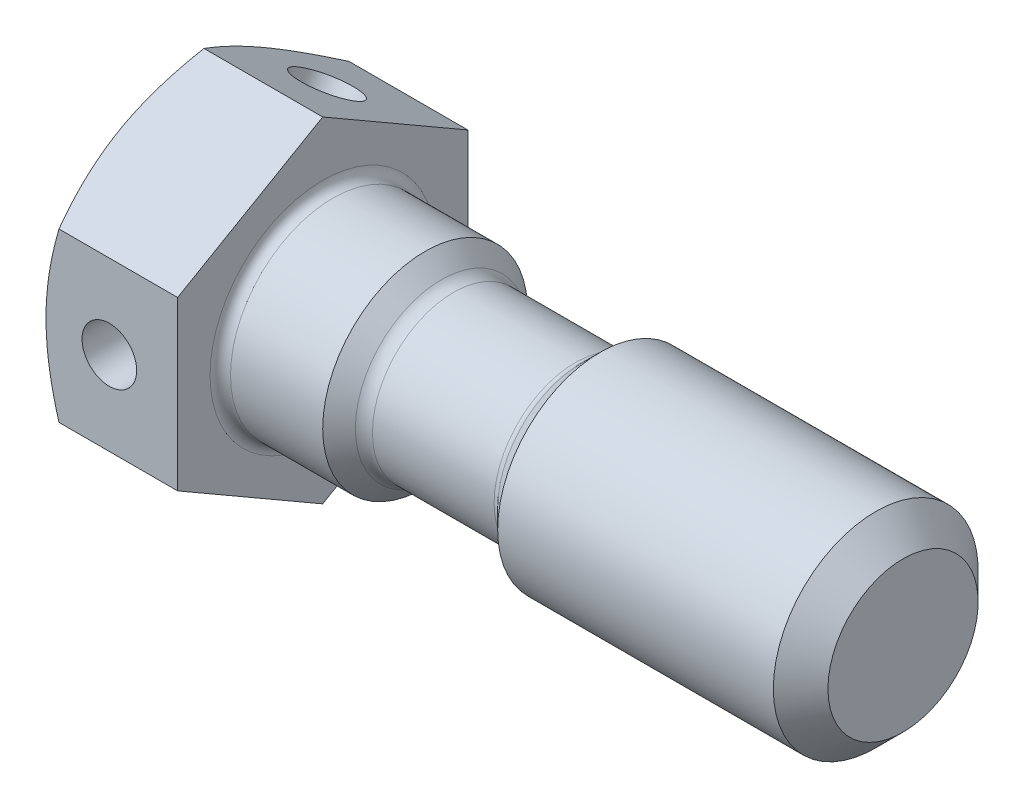
SolidWorks part; units mm, degrees
material "Простая углеродистая сталь"
ref_plane "Спереди" through (0, 0, 0) normal (0, 0, 1) x (1, 0, 0)
ref_plane "Сверху" through (0, 0, 0) normal (0, 1, 0) x (1, 0, 0)
ref_plane "Справа" through (0, 0, 0) normal (1, 0, 0) x (0, 0, -1)
sketch "Эскиз1" plane through (0, 0, 0) normal (0, 0, 1) x (1, 0, 0)
  line L0 (0, 0) -> (41.4975, 0) construction
  line L1 (0, 0) -> (0, 6)
  line L2 (0, 6) -> (6, 6)
  line L3 (6, 6) -> (6.9571, 5.0429)
  line L4 (7.6642, 4.75) -> (14.7929, 4.75)
  line L5 (15.1464, 4.8964) -> (16.25, 6)
  line L6 (16.25, 6) -> (32.4, 6)
  line L7 (34, 4.4) -> (34, 0)
  line L8 (34, 0) -> (0, 0)
  line L9 (32.4, 6) -> (34, 4.4)
  arc A0 (7.6642, 4.75) -> (6.9571, 5.0429) centre (7.6642, 5.75) cw
  arc A1 (15.1464, 4.8964) -> (14.7929, 4.75) centre (14.7929, 5.25) cw
  point P3 (34, 6)
  point P16 (15, 4.75)
  dimension "D10" = 1
  dimension "D11" = 0.5
  dimension "D1" = 12
  dimension "D2" = 9.5
  dimension "D3" = 12
  dimension "D4" = 45
  dimension "D5" = 6
  dimension "D6" = 19
  dimension "D7" = 34
  dimension "D8" = 1.6
  dimension "D9" = 45
revolve "Повернуть1" add sketch "Эскиз1" angle 360 about L0
cosmetic thread "Условное изображение резьбы1" parameters "D2"=10.072
sketch "Эскиз2" plane through (0, 0, 0) normal (-1, 0, 0) x (0, 0, 1)
  line L0 (-8.5, 0) -> (8.5, 0) construction
  line L1 (0, -9.815) -> (0, 9.815) construction
  line L3 (0, -9.815) -> (8.5, -4.9075)
  line L4 (8.5, -4.9075) -> (8.5, 4.9075)
  line L5 (8.5, 4.9075) -> (0, 9.815)
  line L6 (0, 9.815) -> (-8.5, 4.9075)
  line L7 (-8.5, 4.9075) -> (-8.5, -4.9075)
  line L8 (-8.5, -4.9075) -> (0, -9.815)
  circle A0 centre (0, 0) radius 9.815 construction
  point P6 (0, 0)
  dimension "D1" = 17
extrude "Бобышка-Вытянуть1" add sketch "Эскиз2" along normal blind 8
sketch "Эскиз3" plane through (-8, 0, 0) normal (-1, 0, 0) x (0, 0, 1)
  circle A0 centre (0, 0) radius 8
  dimension "D1" = 16
extrude "Вырез-Вытянуть1" cut sketch "Эскиз3" against normal through all draft 60 flip side to cut
fillet "Скругление1" radius 0.6 1 edges at (0, 0, 6)
sketch "Эскиз4" plane through (0, 0, 8.5) normal (0, 0, 1) x (1, 0, 0)
  line L0 (-9.9529, 0) -> (8.4534, 0) construction
  line L1 (-8, 8) -> (-8, -8) construction
  circle A0 centre (-4, 0) radius 1.6
  dimension "D1" = 3.2
  dimension "D2" = 4
extrude "Вырез-Вытянуть2" cut sketch "Эскиз4" against normal through all
sketch "Эскиз5" plane through (0, -7.3612, 4.25) normal (0, -0.866, 0.5) x (1, 0, 0)
  line L0 (-10.0003, 0) -> (5.1327, 0) construction
  line L1 (-8, 8) -> (-8, -8) construction
  circle A0 centre (-4, 0) radius 1.75
  dimension "D1" = 3.5
  dimension "D2" = 4
extrude "Вырез-Вытянуть3" cut sketch "Эскиз5" against normal through all
